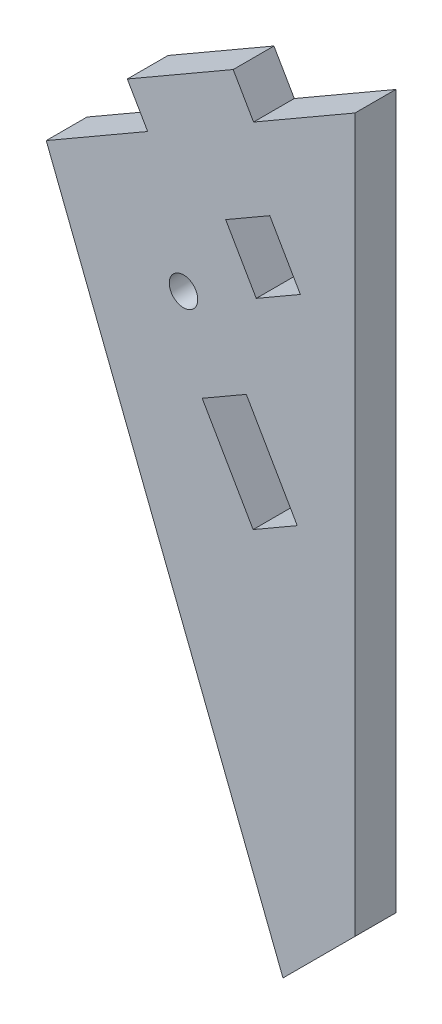
SolidWorks part; units mm, degrees
ref_plane "前视基准面" through (0, 0, 0) normal (0, 0, 1) x (1, 0, 0)
ref_plane "上视基准面" through (0, 0, 0) normal (0, 1, 0) x (1, 0, 0)
ref_plane "右视基准面" through (0, 0, 0) normal (1, 0, 0) x (0, 0, -1)
sketch "草图1" plane through (0, 0, 0) normal (0, 0, 1) x (1, 0, 0)
  line L0 (-15.1554, 17.5) -> (15.1554, -35)
  line L1 (15.1554, 35) -> (15.1554, -35)
  line L2 (15.1554, 35) -> (-15.1554, 17.5)
extrude "凸台-拉伸1" add sketch "草图1" along normal blind 4
sketch "草图3" plane through (-11.3666, 19.6875, 0) normal (-0.5, 0.866, 0) x (0.866, 0.5, 0)
  line L0 (13.125, -4) -> (7.125, -4)
  line L1 (7.125, -4) -> (7.125, 0)
  line L2 (7.125, 0) -> (19.125, 0)
  line L3 (19.125, 0) -> (19.125, -4)
  line L4 (30.625, 0) -> (-4.375, 0)
  line L5 (-4.375, 0) -> (-4.375, -4)
  line L6 (-4.375, -4) -> (30.625, -4)
  line L7 (30.625, -4) -> (30.625, 0)
  line L8 (19.125, 0) -> (7.125, 0)
  line L10 (7.125, -4) -> (19.125, -4)
  line M5 (30.625, 0) -> (-4.375, 0)
  line M7 (-4.375, -4) -> (30.625, -4)
  dimension "D1" = 0
extrude "凸台-拉伸2" add sketch "草图3" along normal blind 5 contours L3 L1 M5 M7
extrude "切除-拉伸1" cut sketch "草图4" against normal blind 5
sketch "草图4" plane through (117.0136, -126.1336, 5) normal (0, 0, 1) x (1, 0.0076, 0)
  line L8 (-106.5887, 124.0329) -> (-111.5227, 132.7309)
  line L9 (-111.5227, 132.7309) -> (-115.8717, 130.2639)
  line L10 (-115.8717, 130.2639) -> (-110.9377, 121.5659)
  line L11 (-110.9377, 121.5659) -> (-106.5887, 124.0329)
extrude "切除-拉伸3" cut sketch "草图6" against normal blind 5
sketch "草图6" plane through (116.7508, -91.5803, 5) normal (0, 0, 1) x (1, 0.0076, 0)
  line L8 (-113.4423, 112.0336) -> (-110.4819, 106.8148)
  line L9 (-110.4819, 106.8148) -> (-106.1329, 109.2818)
  line L10 (-106.1329, 109.2818) -> (-109.0933, 114.5006)
  line L11 (-109.0933, 114.5006) -> (-113.4423, 112.0336)
sketch "草图7" plane through (0, 0, 0) normal (0, 0, -1) x (-1, 0, 0)
  line L0 (15.1554, 17.5) -> (-15.1554, -35) construction
  line L1 (15.1554, 17.5) -> (-15.1554, -35)
  line L2 (-15.1554, -35) -> (-8.0844, -42.0711)
  line L3 (-8.0844, -42.0711) -> (15.1554, 17.5)
extrude "凸台-拉伸3" add sketch "草图7" against normal up to surface (4 mm away) up to face at (6.1247, 18.2391, 4)
sketch "草图8" plane through (-13.8666, 24.0176, 0) normal (-0.5, 0.866, 0) x (0.866, 0.5, 0)
  line L4 (19.125, -4) -> (19.125, 0)
  line L5 (19.125, 0) -> (7.125, 0)
  line L6 (7.125, 0) -> (7.125, -4)
  line L7 (7.125, -4) -> (19.125, -4)
  line L8 (19.125, -4) -> (19.125, 0)
  line L9 (19.125, 0) -> (7.125, 0)
  line L10 (7.125, 0) -> (7.125, -4)
  line L11 (7.125, -4) -> (19.125, -4)
  dimension "D1" = 0
extrude "切除-拉伸4" cut sketch "草图8" against normal blind 1
extrude "切除-拉伸5" cut sketch "草图9" against normal blind 4
sketch "草图9" plane through (116.7447, -90.7798, 0) normal (0, 0, -1) x (-1, -0.0076, 0)
  circle A0 centre (117.6444, 103.101) radius 1.4
